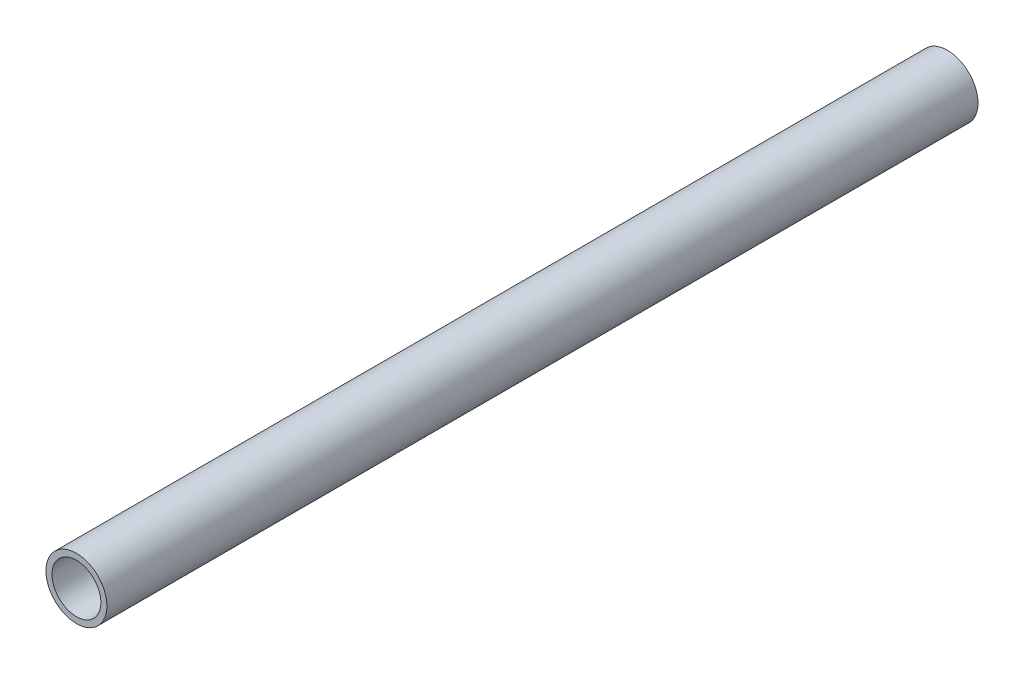
SolidWorks part; units mm, degrees
ref_plane "Front Plane" through (0, 0, 0) normal (0, 0, 1) x (1, 0, 0)
ref_plane "Top Plane" through (0, 0, 0) normal (0, 1, 0) x (1, 0, 0)
ref_plane "Right Plane" through (0, 0, 0) normal (1, 0, 0) x (0, 0, -1)
sketch "Sketch1" plane through (0, 0, 0) normal (0, 0, 1) x (1, 0, 0)
  line L0 (8.5598, 0) -> (10.668, 0) construction
  circle A0 centre (0, 0) radius 10.668 construction
  circle A1 centre (0, 0) radius 8.5598 construction
  dimension "ID" = 17.1196
  dimension "OD" = 21.336
  dimension "Wall Thickness" = 2.1082
sketch "Sketch2" plane through (0, 0, 0) normal (1, 0, 0) x (0, 0, -1)
  line L0 (-152.4, 0) -> (152.4, 0) construction
  line L1 (-131.0005, 10.668) -> (-131.0005, -10.668) construction
  line L2 (131.0005, 10.668) -> (131.0005, -10.668) construction
  point P4 (0, 0)
  point P8 (-131.0005, 0)
  point P11 (131.0005, 0)
  dimension "Length" = 304.8
  dimension "D1" = 21.3995
  dimension "D2" = 21.3995
  dimension "D3" = 21.336
sketch "Sketch3" plane through (0, 0, 0) normal (0, 0, 1) x (1, 0, 0)
  circle A0 centre (0, 0) radius 10.668
  circle A1 centre (0, 0) radius 10.668 construction
  circle A2 centre (0, 0) radius 8.5598 construction
  circle A3 centre (0, 0) radius 8.5598
extrude "Boss-Extrude1" add sketch "Sketch3" along normal up to vertex (152.4 mm away) and the other way up to vertex (152.4 mm away) up to point (0, 0, 152.4) other way up to point (0, 0, -152.4)
equation "\"D1@Sketch2\"=If(\"ID@Sketch1\">6,5.5,(\"ID@Sketch1\"*1.25))"
equation "\"D2@Sketch2\"=\"D1@Sketch2\""
equation "\"D3@Sketch2\"= \"OD@Sketch1\""
